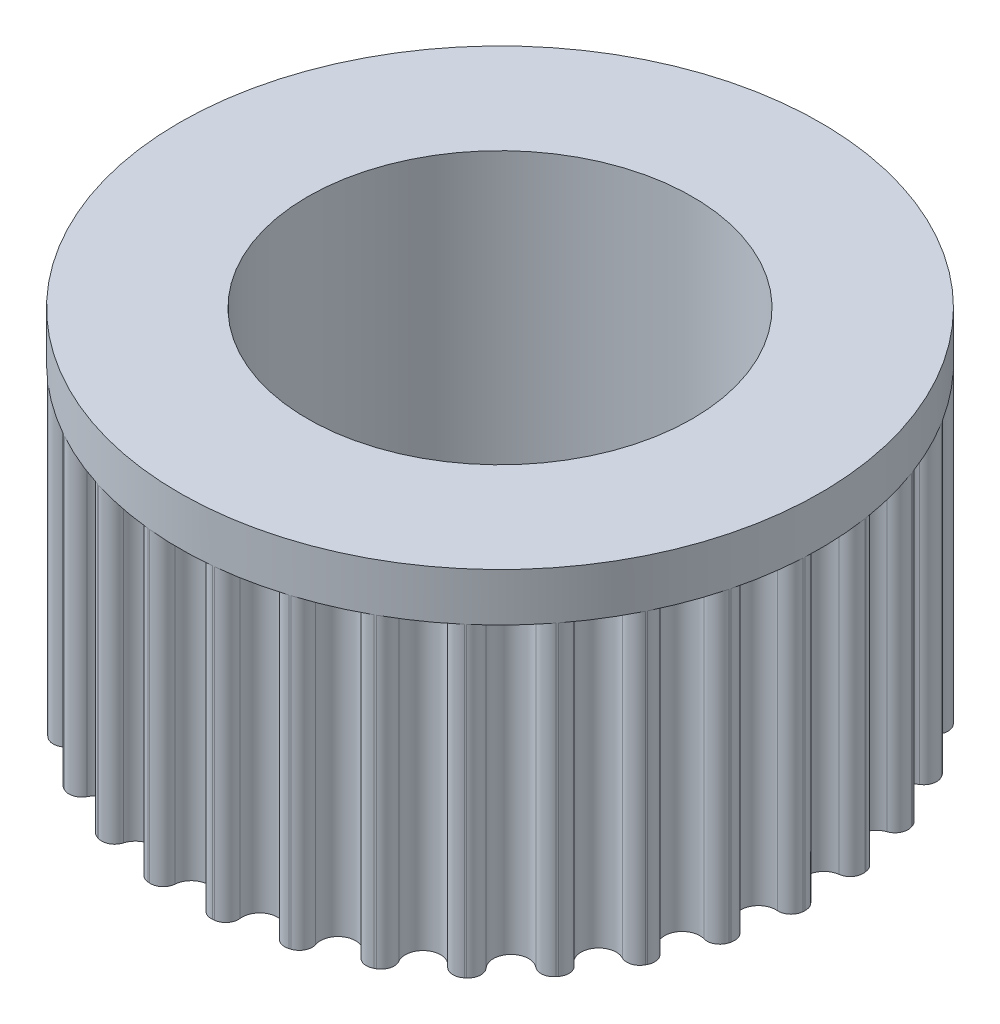
SolidWorks part; units mm, degrees
ref_plane "Front plan" through (0, 0, 0) normal (0, 0, 1) x (1, 0, 0)
ref_plane "Top plan" through (0, 0, 0) normal (0, 1, 0) x (1, 0, 0)
ref_plane "Right plan" through (0, 0, 0) normal (1, 0, 0) x (0, 0, -1)
sketch "Skica2" plane through (0, 0, 0) normal (0, 0, 1) x (1, 0, 0)
  line L1 (6, 4.775) -> (6, -4.775)
  line L3 (0, -9) -> (0, 9) construction
  line L7 (11, 3.775) -> (10, 3.775)
  line L8 (10, 3.775) -> (10, -3.775)
  line L9 (11, 3.775) -> (11, 4.775)
  line L12 (11, -4.775) -> (7.5594, -4.775)
  line L13 (11, 4.775) -> (7.0575, 4.775)
  line L14 (11, -4.775) -> (11, -3.775)
  line L15 (10, -3.775) -> (11, -3.775)
  line L17 (7.0575, 4.775) -> (6, 4.775)
  line L18 (7.5594, -4.775) -> (6, -4.775)
  point P0 (7.5594, -4.775)
  point P3 (6, 0)
  point P7 (0, 0)
  dimension "D3" = 20
  dimension "D1" = 12
  dimension "D2" = 9.55
  dimension "D4" = 1
  dimension "D5" = 1
revolve "Revolute" add sketch "Skica2" angle 360 about L3
sketch "Sketch2" plane through (0, 3.775, 0) normal (0, -1, 0) x (1, 0, 0)
  line L0 (0, 0) -> (0, 9.6272) construction
  line L1 (0, 0) -> (3.372, 9.4143) construction
  line L3 (0, 0) -> (-2.5191, 9.6775) construction
  circle A1 centre (0, 0) radius 9.0772 construction
  circle A2 centre (0, 0) radius 9.6 construction
  arc A3 (-0.5483, 9.5843) -> (0.5483, 9.5843) centre (0, 9.6272) ccw
  arc A7 (-0.9866, 9.9512) -> (-2.5191, 9.6775) centre (0, 0) ccw
  arc A8 (0, 11.1914) -> (2.5191, 9.6775) centre (0.9701, 9.9528) cw
  circle A9 centre (0, 0) radius 10 construction
  arc A10 (0.9866, 9.9512) -> (2.5191, 9.6775) centre (0, 0) cw
  arc A11 (0.9866, 9.9512) -> (0.5483, 9.5843) centre (0.9471, 9.5532) ccw
  arc A12 (0, 11.1914) -> (-2.5191, 9.6775) centre (-0.9701, 9.9528) ccw
  arc A13 (-0.9866, 9.9512) -> (-0.5483, 9.5843) centre (-0.9471, 9.5532) cw
  dimension "D2" = 0.8
  dimension "D4" = 0.55
  dimension "D6" = 20
  dimension "D3" = 1.5733
  dimension "D1" = 0.4
extrude "Cut-Extrude3" cut sketch "Sketch2" along normal mid plane 50
pattern_circular "CirPattern1" count 31 over 360 about axis through (0, 0, 0) along (0, 1, 0) of "Cut-Extrude3"
ref_plane "Plane1" through (0, 1.575, 0) normal (0, -1, 0) x (-1, 0, 0)
sketch "Sketch3" plane through (0, 4.775, 0) normal (0, 1, 0) x (1, 0, 0)
  circle A0 centre (0, 0) radius 10
  circle A1 centre (0, 0) radius 6
  circle A2 centre (0, 0) radius 6 construction
extrude "Boss-Extrude1" add sketch "Sketch3" along normal blind 1.5
equation "\"`\"=2"
equation "\"D6@Sketch2\"= \"D3@Skica2\""
